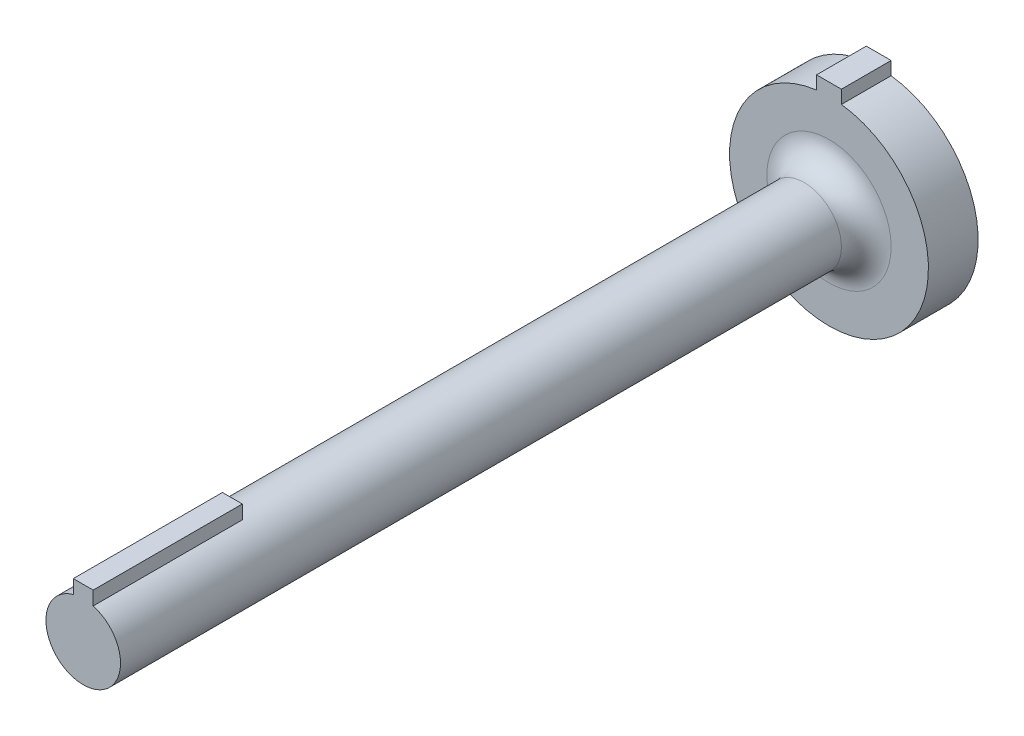
SolidWorks part; units mm, degrees
ref_plane "Front Plane" through (0, 0, 0) normal (0, 0, 1) x (1, 0, 0)
ref_plane "Top Plane" through (0, 0, 0) normal (0, 1, 0) x (1, 0, 0)
ref_plane "Right Plane" through (0, 0, 0) normal (1, 0, 0) x (0, 0, -1)
sketch "Sketch2" plane through (0, 0, 0) normal (0, 1, 0) x (1, 0, 0)
  line L0 (-1000, 0) -> (49000, 0) construction
  line L1 (0, 0) -> (0, -605.612) construction
  line L3 (-6.35, 0) -> (6.35, 0)
  line L4 (-6.35, 0) -> (-6.35, -25.4)
  line L5 (-6.35, -25.4) -> (6.35, -25.4)
  line L6 (6.35, 0) -> (6.35, -25.4)
  dimension "D1" = 12.7
  dimension "D2" = 25.4
extrude "Boss-Extrude2" add sketch "Sketch2" along normal blind 57.15
sketch "Sketch3" plane through (0, 0, 0) normal (0, 1, 0) x (1, 0, 0)
  line L0 (-1000, 0) -> (49000, 0) construction
  line L1 (0, -1000) -> (0, 49000) construction
  line L3 (-5.08, -406.4) -> (5.08, -406.4)
  line L4 (-5.08, -406.4) -> (-5.08, -330.2)
  line L5 (-5.08, -330.2) -> (5.08, -330.2)
  line L6 (5.08, -406.4) -> (5.08, -330.2)
  dimension "D1" = 5.08
  dimension "D2" = 10.16
  dimension "D3" = 76.2
  dimension "D4" = 406.4
extrude "Boss-Extrude3" add sketch "Sketch3" along normal blind 25.4 separate body
sketch "Sketch4" plane through (0, 0, 0) normal (1, 0, 0) x (0, 0, -1)
  line L0 (-1000, 0) -> (49000, 0) construction
  line L1 (0, -1000) -> (0, 49000) construction
  line L2 (0, 0) -> (0, 50.8)
  line L3 (0, 50.8) -> (-25.4, 50.8)
  line L4 (-25.4, 57.15) -> (-25.4, 0) construction
  line L5 (-25.4, 50.8) -> (-25.4, 31.75)
  line L6 (-38.1, 19.05) -> (-406.4, 19.05)
  line L7 (-406.4, 25.4) -> (-406.4, 0) construction
  line L8 (-406.4, 19.05) -> (-406.4, 0)
  line L9 (-406.4, 0) -> (0, 0)
  arc A0 (-25.4, 31.75) -> (-38.1, 19.05) centre (-38.1, 31.75) cw
  point P19 (-25.4, 19.05)
  dimension "D3" = 12.7
  dimension "D1" = 50.8
  dimension "D2" = 19.05
revolve "Revolve2" add sketch "Sketch4" angle 360 about L0
